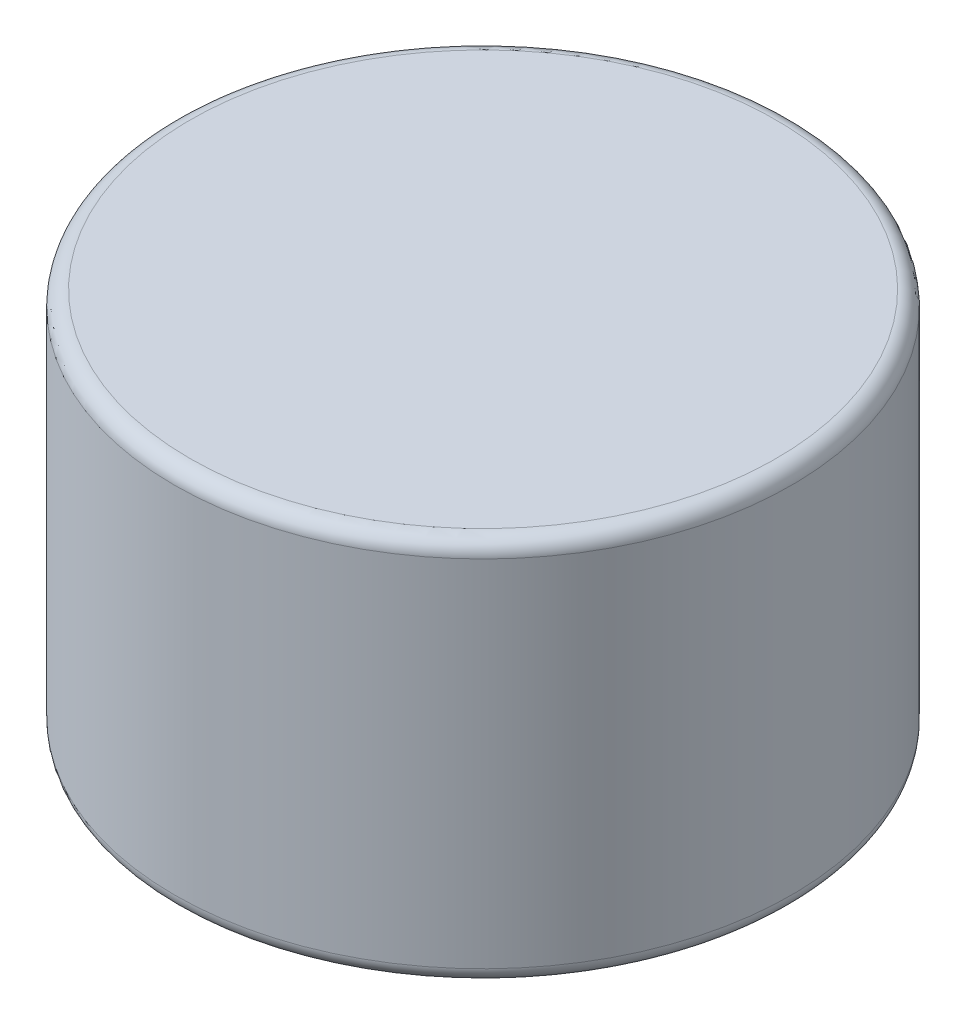
SolidWorks part; units mm, degrees
ref_plane "Front" through (0, 0, 0) normal (0, 0, 1) x (1, 0, 0)
ref_plane "Top" through (0, 0, 0) normal (0, 1, 0) x (1, 0, 0)
ref_plane "Right" through (0, 0, 0) normal (1, 0, 0) x (0, 0, -1)
sketch "Эскиз1" plane through (0, 0, 0) normal (0, 1, 0) x (1, 0, 0)
  circle A0 centre (0, 0) radius 4
  dimension "D1" = 8
extrude "Бобышка-Вытянуть1" add sketch "Эскиз1" along normal blind 5
fillet "Скругление1" radius 0.2 2 edges at (0, 0, 4) (0, 5, 4)
